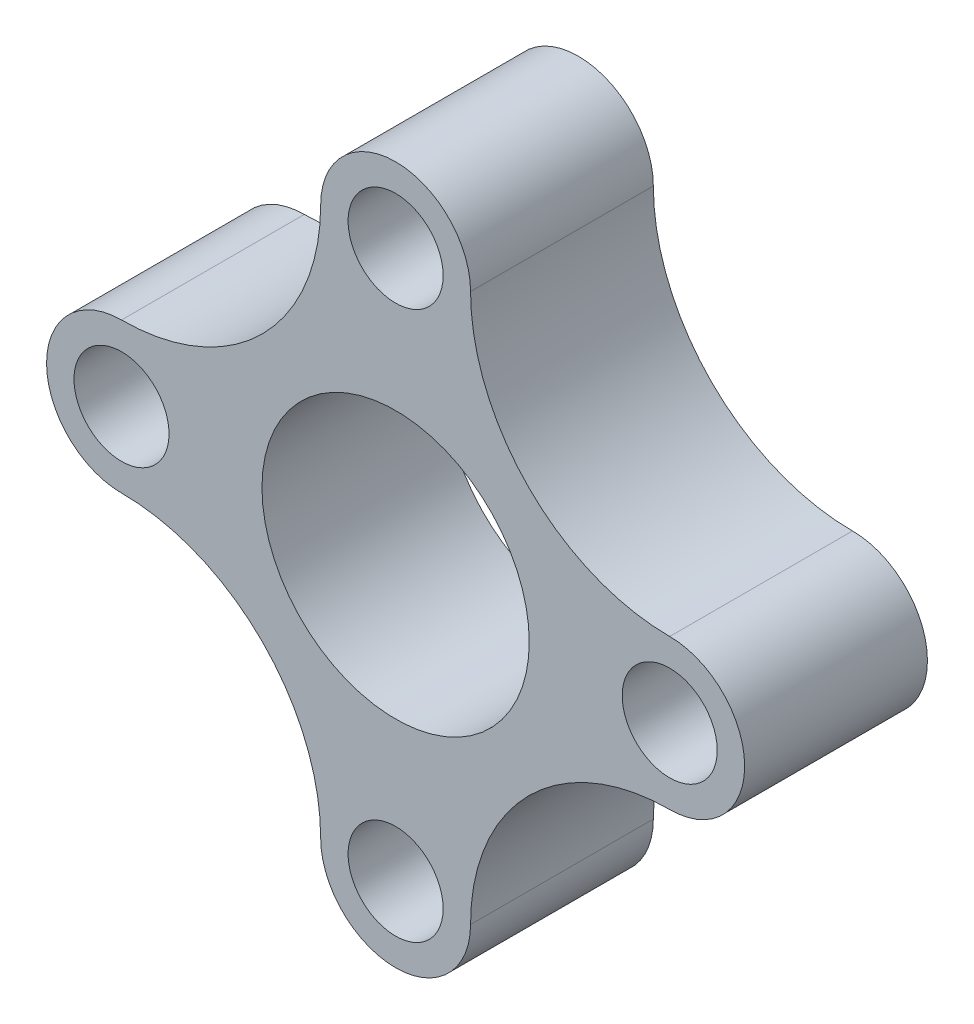
SolidWorks part; units mm, degrees
ref_plane "xy" through (0, 0, 0) normal (0, 0, 1) x (1, 0, 0)
ref_plane "xz" through (0, 0, 0) normal (0, 1, 0) x (1, 0, 0)
ref_plane "yz" through (0, 0, 0) normal (1, 0, 0) x (0, 0, -1)
sketch "Skizze1" plane through (0, 0, 0) normal (0, 0, 1) x (1, 0, 0)
  line L0 (0, 19.0958) -> (0, 0)
  line L1 (0, 0) -> (8.9958, 0) construction
  line L2 (0, 0) -> (0, 8.9958) construction
  line L3 (0, 8.9958) -> (8.9958, 8.9958) construction
  line L4 (8.9958, 0) -> (8.9958, 8.9958) construction
  line L5 (0, 0) -> (19.0958, 0)
  line L6 (5.4673, 12.5242) -> (12.5242, 5.4673) construction
  circle A0 centre (14.9958, 0) radius 6 construction
  circle A1 centre (0, 14.9958) radius 6 construction
  circle A2 centre (0, 14.9958) radius 2.6 construction
  circle A3 centre (14.9958, 0) radius 2.6 construction
  arc A4 (0, 19.0958) -> (4.1, 14.9958) centre (0, 14.9958) cw
  arc A5 (19.0958, 0) -> (14.9958, 4.1) centre (14.9958, 0) ccw
  arc A6 (4.1, 14.9958) -> (14.9958, 4.1) centre (14.9958, 14.9958) ccw
  dimension "D2" = 12
  dimension "D3" = 5.2
  dimension "D4" = 1.5
  dimension "D1" = 9.98
extrude "Aufsatz-Linear austragen1" add sketch "Skizze1" along normal blind 10
mirror "Spiegeln1" about plane through (0, 0, 0) normal (0, 1, 0) of bodies 101
mirror "Spiegeln2" about plane through (0, 0, 0) normal (1, 0, 0) of bodies 102
sketch "Skizze2" plane through (0, 0, 0) normal (0, 0, 1) x (1, 0, 0)
  line L0 (-14.9958, 0) -> (0, 14.9958) construction
  line L1 (-14.9958, 0) -> (0, -14.9958) construction
  line L2 (0, 14.9958) -> (14.9958, 0) construction
  line L3 (0, -14.9958) -> (14.9958, 0) construction
  line L4 (-14.9958, 0) -> (14.9958, 0) construction
  line L5 (0, 14.9958) -> (0, -14.9958) construction
  circle A0 centre (0, 14.9958) radius 2.6
  circle A1 centre (14.9958, 0) radius 2.6
  circle A2 centre (0, -14.9958) radius 2.6
  circle A3 centre (-14.9958, 0) radius 2.6
  circle A4 centre (0, 14.9958) radius 2.6 construction
  point P1 (0, 0)
extrude "Schnitt-Linear austragen2" cut sketch "Skizze2" along normal blind 10
sketch "Skizze3" plane through (0, 0, 0) normal (0, 0, 1) x (1, 0, 0)
  line L0 (0, 19.0958) -> (0, 0) construction
  line L1 (-7.2913, 7.2913) -> (-5.17, 5.17) construction
  circle A0 centre (0, 0) radius 7.3115
  circle A1 centre (0, 14.9958) radius 2.6 construction
  arc A2 (-14.9958, 4.1) -> (-4.1, 14.9958) centre (-14.9958, 14.9958) ccw construction
  point P3 (0, 7.3115)
  point P4 (0, 12.3958)
  point P5 (-7.2913, 7.2913)
  dimension "D1" = 3
extrude "Schnitt-Linear austragen4" cut sketch "Skizze3" along normal blind 10
